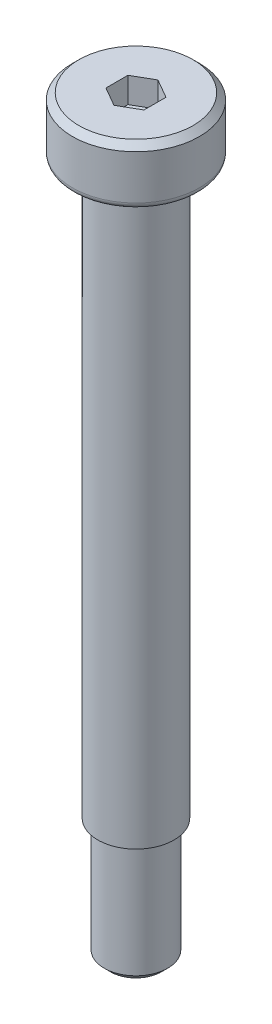
SolidWorks part; units mm, degrees
material "Plain Carbon Steel"
ref_plane "Front Plane" through (0, 0, 0) normal (0, 0, 1) x (1, 0, 0)
ref_plane "Top Plane" through (0, 0, 0) normal (0, 1, 0) x (1, 0, 0)
ref_plane "Right Plane" through (0, 0, 0) normal (1, 0, 0) x (0, 0, -1)
sketch "Sketch1" plane through (0, 0, 0) normal (0, 0, 1) x (1, 0, 0)
  line L0 (0, 0) -> (5, 0)
  line L1 (5, 0) -> (5, -4.5)
  line L2 (5, -4.5) -> (2.75, -4.5)
  line L3 (2.75, -4.5) -> (2.75, -4.75)
  line L4 (2.75, -4.75) -> (3, -4.75)
  line L5 (3, -4.75) -> (3, -49.5)
  line L6 (3, -49.5) -> (2.5, -49.5)
  line L7 (2.5, -49.5) -> (2.5, -59)
  line L8 (2.5, -59) -> (0, -59)
  line L9 (0, -59) -> (0, 0)
  line L10 (0, 5) -> (0, -64) construction
  dimension "D1" = 5
  dimension "D2" = 5
  dimension "D3" = 5
  dimension "D4" = 6
  dimension "D5" = 0.25
  dimension "D6" = 10
  dimension "Length" = 45
  dimension "D8" = 4.5
  dimension "D9" = 0.25
  dimension "D10" = 9.5
revolve "Revolve1" add sketch "Sketch1" angle 360 about L10
sketch "Sketch2" plane through (0, 0, 0) normal (0, 1, 0) x (1, 0, 0)
  line L1 (0, -1.7321) -> (1.5, -0.866)
  line L2 (1.5, -0.866) -> (1.5, 0.866)
  line L3 (1.5, 0.866) -> (0, 1.7321)
  line L4 (0, 1.7321) -> (-1.5, 0.866)
  line L5 (-1.5, 0.866) -> (-1.5, -0.866)
  line L6 (-1.5, -0.866) -> (0, -1.7321)
  circle A0 centre (0, 0) radius 1.5 construction
  dimension "D1" = 3
extrude "Cut-Extrude1" cut sketch "Sketch2" against normal blind 2
chamfer "Chamfer1" distance 0.5 angle 45 1 edges at (-5, 0, 0)
fillet "Fillet1" radius 0.5 1 edges at (-5, -4.5, 0)
chamfer "Chamfer2" distance 0.5 angle 45 1 edges at (-2.5, -59, 0)
